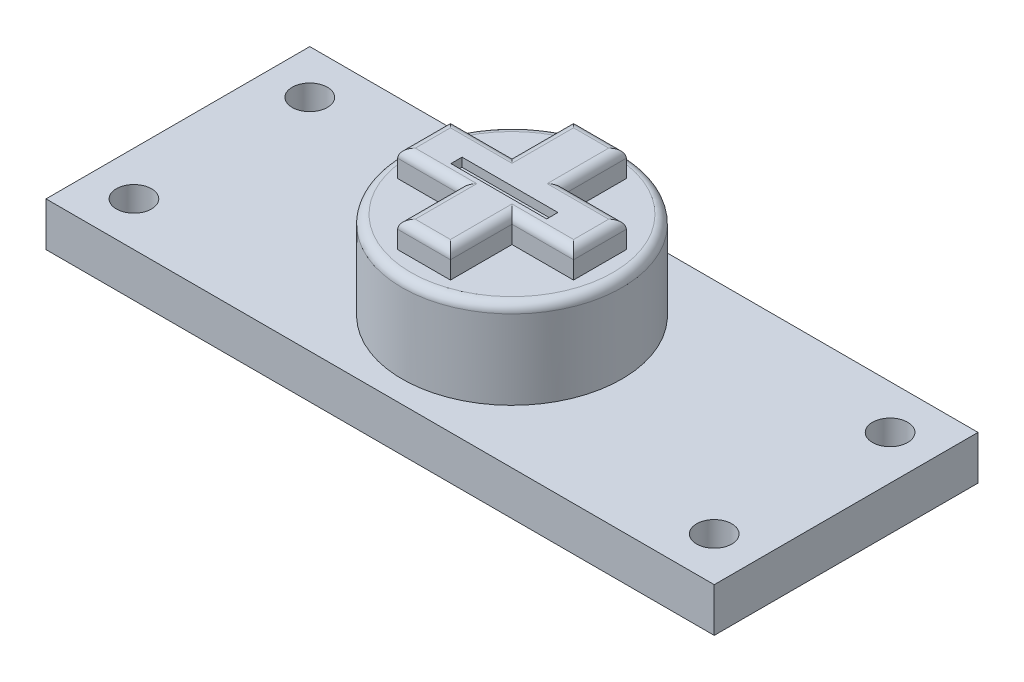
SolidWorks part; units mm, degrees
ref_plane "Front Plane" through (0, 0, 0) normal (0, 0, 1) x (1, 0, 0)
ref_plane "Top Plane" through (0, 0, 0) normal (0, 1, 0) x (1, 0, 0)
ref_plane "Right Plane" through (0, 0, 0) normal (1, 0, 0) x (0, 0, -1)
sketch "Sketch1" plane through (0, 0, 0) normal (0, 1, 0) x (1, 0, 0)
  line L1 (-3800, 1500) -> (3800, 1500)
  line L2 (-3800, 1500) -> (-3800, -1500)
  line L3 (-3800, -1500) -> (3800, -1500)
  line L4 (3800, 1500) -> (3800, -1500)
  line L5 (-3800, 1500) -> (3800, -1500) construction
  line L6 (-3800, -1500) -> (3800, 1500) construction
  point P0 (0, 0)
  dimension "D1" = 7600
  dimension "D2" = 3000
extrude "Boss-Extrude1" add sketch "Sketch1" along normal blind 500 contours L2 L3 L4 L1
sketch "Sketch2" plane through (0, 500, 0) normal (0, 1, 0) x (1, 0, 0)
  line L0 (-3800, 1500) -> (3800, 1500) construction
  line L1 (3800, 1500) -> (3800, -1500) construction
  line L2 (-3800, -1500) -> (3800, -1500) construction
  line L3 (-3800, 1500) -> (-3800, -1500) construction
  circle A0 centre (-3300, -1000) radius 200
  circle A1 centre (-3300, 1000) radius 200
  circle A2 centre (3300, 1000) radius 200
  circle A3 centre (3300, -1000) radius 200
  dimension "D1" = 400
  dimension "D2" = 400
  dimension "D3" = 400
  dimension "D4" = 400
  dimension "D5" = 500
  dimension "D6" = 500
  dimension "D7" = 500
  dimension "D8" = 500
  dimension "D9" = 500
  dimension "D10" = 500
  dimension "D11" = 500
  dimension "D12" = 500
extrude "Cut-Extrude1" cut sketch "Sketch2" against normal blind 1000
sketch "Sketch3" plane through (0, 500, 0) normal (0, 1, 0) x (1, 0, 0)
  circle A0 centre (0, 0) radius 1250
  dimension "D1" = 2500
extrude "Boss-Extrude2" add sketch "Sketch3" along normal blind 1000
sketch "Sketch4" plane through (0, 1500, 0) normal (0, 1, 0) x (1, 0, 0)
  line L0 (-300, -300) -> (-300, -1000)
  line L1 (-300, 1000) -> (300, 1000)
  line L2 (-300, 1000) -> (-300, 300)
  line L3 (-300, -1000) -> (300, -1000)
  line L4 (300, 1000) -> (300, 300)
  line L5 (-300, 1000) -> (300, -1000) construction
  line L6 (-300, -1000) -> (300, 1000) construction
  line L7 (1000, -300) -> (300, -300)
  line L8 (1000, -300) -> (1000, 300)
  line L9 (1000, 300) -> (300, 300)
  line L10 (-1000, -300) -> (-1000, 300)
  line L11 (1000, -300) -> (-1000, 300) construction
  line L12 (1000, 300) -> (-1000, -300) construction
  line L13 (300, -300) -> (300, -1000)
  line L14 (-300, -300) -> (-1000, -300)
  line L15 (-300, 300) -> (-1000, 300)
  point P0 (0, 0)
  point P6 (0, 0)
  dimension "D1" = 600
  dimension "D2" = 600
  dimension "D3" = 2000
  dimension "D4" = 2000
extrude "Boss-Extrude3" add sketch "Sketch4" along normal blind 300
fillet "Fillet1" radius 100 12 edges at (0, 1800, 1000) (-300, 1800, 650) (-650, 1800, 300) (-1000, 1800, 0) (-650, 1800, -300) (-300, 1800, -650) (0, 1800, -1000) (300, 1800, -650) (650, 1800, -300) (1000, 1800, 0) (650, 1800, 300) (300, 1800, 650)
fillet "Fillet2" radius 100 1 edges at (0, 1500, 1250)
sketch "Sketch6" plane through (0, 1800, 0) normal (0, 1, 0) x (1, 0, 0)
  line L0 (-900, -200) -> (-200, -200) construction
  line L1 (-545.25, -23) -> (545.25, -23)
  line L2 (-545.25, -23) -> (-545.25, -150)
  line L3 (-545.25, -150) -> (545.25, -150)
  line L4 (545.25, -23) -> (545.25, -150)
  point P6 (0, 0)
  dimension "D1" = 1090.5
  dimension "D2" = 127
  dimension "D3" = 177
extrude "Cut-Extrude2" cut sketch "Sketch6" against normal blind 100
